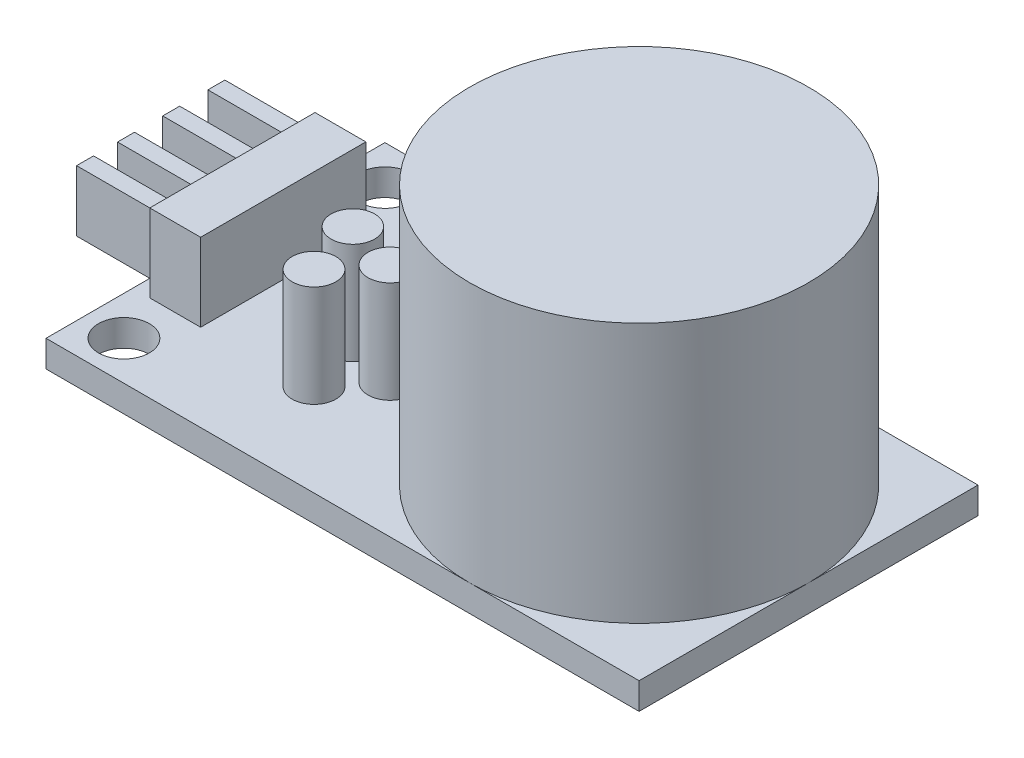
SolidWorks part; units mm, degrees
ref_plane "Front Plane" through (0, 0, 0) normal (0, 0, 1) x (1, 0, 0)
ref_plane "Top Plane" through (0, 0, 0) normal (0, 1, 0) x (1, 0, 0)
ref_plane "Right Plane" through (0, 0, 0) normal (1, 0, 0) x (0, 0, -1)
sketch "Sketch1" plane through (0, 0, 0) normal (0, 1, 0) x (1, 0, 0)
  line L1 (0, 0) -> (35, 0)
  line L2 (0, 0) -> (0, 20)
  line L3 (0, 20) -> (35, 20)
  line L4 (35, 0) -> (35, 20)
  circle A0 centre (2.3, 17.7) radius 1.5
  circle A1 centre (2.3, 2.3) radius 1.5
  dimension "D3" = 3
  dimension "D4" = 2.3
  dimension "D6" = 2.3
  dimension "D7" = 2.3
  dimension "D8" = 3
  dimension "D1" = 20
  dimension "D2" = 35
  dimension "D5" = 2.3
extrude "Boss-Extrude1" add sketch "Sketch1" along normal blind 1.57
sketch "Sketch2" plane through (0, 1.57, 0) normal (0, 1, 0) x (1, 0, 0)
  line L0 (35, 0) -> (35, 20) construction
  circle A0 centre (25, 10) radius 10
  dimension "D1" = 10
extrude "Boss-Extrude2" add sketch "Sketch2" along normal blind 15.34
sketch "Sketch3" plane through (0, 1.57, 0) normal (0, 1, 0) x (1, 0, 0)
  line L0 (0, 0) -> (25, 0) construction
  line L1 (1, 14.875) -> (4, 14.875)
  line L2 (1, 14.875) -> (1, 5.125)
  line L3 (1, 5.125) -> (4, 5.125)
  line L4 (4, 14.875) -> (4, 5.125)
  line L5 (0, 20) -> (0, 0) construction
  line L6 (25, 20) -> (0, 20) construction
  dimension "D1" = 9.75
  dimension "D2" = 5.125
  dimension "D3" = 1
  dimension "D4" = 3
  dimension "D5" = 5.125
extrude "Boss-Extrude3" add sketch "Sketch3" along normal blind 4.6
sketch "Sketch4" plane through (1, 0, 0) normal (-1, 0, 0) x (0, 0, 1)
  line L0 (-14.875, 1.57) -> (-5.125, 1.57) construction
  line L1 (-14.375, 5.67) -> (-5.625, 5.67)
  line L2 (-14.375, 5.67) -> (-14.375, 2.07)
  line L3 (-14.375, 2.07) -> (-5.625, 2.07)
  line L4 (-5.625, 5.67) -> (-5.625, 2.07)
  line L5 (-14.875, 6.17) -> (-5.125, 6.17) construction
  line L6 (-14.875, 6.17) -> (-14.875, 1.57) construction
  line L7 (-5.125, 6.17) -> (-5.125, 1.57) construction
  dimension "D1" = 0.5
  dimension "D2" = 0.5
  dimension "D3" = 0.5
  dimension "D4" = 0.5
extrude "Boss-Extrude4" add sketch "Sketch4" along normal blind 4.82
sketch "Sketch5" plane through (-3.82, 0, 0) normal (-1, 0, 0) x (0, 0, 1)
  line L0 (-5.625, 5.67) -> (-14.375, 5.67) construction
  line L1 (-13.375, 5.67) -> (-11.7083, 5.67)
  line L2 (-13.375, 5.67) -> (-13.375, 2.07)
  line L3 (-13.375, 2.07) -> (-11.7083, 2.07)
  line L4 (-11.7083, 5.67) -> (-11.7083, 2.07)
  line L5 (-14.375, 2.07) -> (-5.625, 2.07) construction
  line L6 (-14.375, 2.07) -> (-5.625, 2.07) construction
  line L7 (-10.7083, 5.67) -> (-9.0417, 5.67)
  line L8 (-10.7083, 5.67) -> (-10.7083, 2.07)
  line L9 (-10.7083, 2.07) -> (-9.0417, 2.07)
  line L10 (-9.0417, 5.67) -> (-9.0417, 2.07)
  line L11 (-5.625, 5.67) -> (-14.375, 5.67) construction
  line L12 (-8.0417, 5.67) -> (-6.625, 5.67)
  line L13 (-8.0417, 5.67) -> (-8.0417, 2.07)
  line L14 (-8.0417, 2.07) -> (-6.625, 2.07)
  line L15 (-6.625, 5.67) -> (-6.625, 2.07)
  line L16 (-14.375, 5.67) -> (-14.375, 2.07) construction
  line L17 (-5.625, 2.07) -> (-5.625, 5.67) construction
  dimension "D1" = 1
  dimension "D2" = 1
  dimension "D3" = 1
  dimension "D4" = 1
  dimension "D5" = 1.6667
  dimension "D6" = 1.6667
  dimension "D7" = 1.4167
extrude "Cut-Extrude1" cut sketch "Sketch5" against normal up to surface (4.82 mm away) up to face at (1, 3.87, -10)
sketch "Sketch6" plane through (0, 1.57, 0) normal (0, 1, 0) x (1, 0, 0)
  circle A0 centre (12.4067, 7.8979) radius 1.2969
  circle A1 centre (11.5774, 12.2105) radius 1.7208
  circle A2 centre (10.3753, 5.4401) radius 1.291
  circle A3 centre (9.3428, 8.7663) radius 1.2848
extrude "Boss-Extrude5" add sketch "Sketch6" along normal blind 6
sketch "Sketch7" plane through (0, 0, 0) normal (0, -1, 0) x (1, 0, 0)
  line L0 (35, -20) -> (0, -20) construction
  line L1 (0, 0) -> (35, 0) construction
  line L2 (35, 0) -> (35, -20) construction
  circle A0 centre (25, -10) radius 2.5
  dimension "D2" = 5
  dimension "D1" = 10
  dimension "D3" = 10
  dimension "D4" = 10
extrude "Boss-Extrude6" add sketch "Sketch7" along normal blind 2
